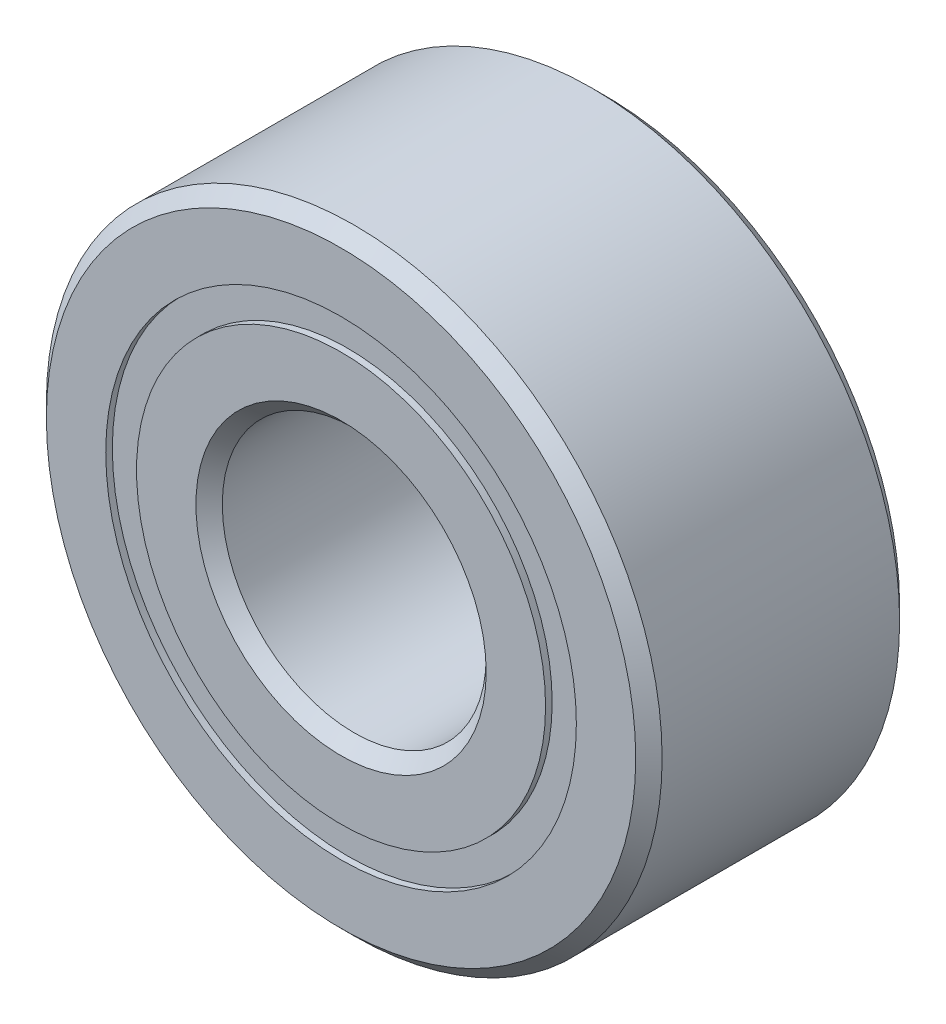
SolidWorks part; units mm, degrees
material "Chrome Stainless Steel"
ref_plane "Front Plane" through (0, 0, 0) normal (0, 0, 1) x (1, 0, 0)
ref_plane "Top Plane" through (0, 0, 0) normal (0, 1, 0) x (1, 0, 0)
ref_plane "Right Plane" through (0, 0, 0) normal (1, 0, 0) x (0, 0, -1)
sketch "Sketch3" plane through (0, 0, 0) normal (0, 1, 0) x (1, 0, 0)
  line L0 (1.5, -1.5) -> (1.5, 1.5)
  line L1 (1.5, 1.5) -> (2.325, 1.5)
  line L2 (2.325, 1.5) -> (2.325, 1.425)
  line L3 (2.325, 1.425) -> (2.675, 1.425)
  line L4 (2.675, 1.425) -> (2.675, 1.5)
  line L5 (2.675, 1.5) -> (3.5, 1.5)
  line L6 (3.5, 1.5) -> (3.5, -1.5)
  line L7 (-55, 0) -> (55, 0) construction
  line L8 (2.675, -1.5) -> (3.5, -1.5)
  line L9 (2.675, -1.425) -> (2.675, -1.5)
  line L10 (2.325, -1.425) -> (2.675, -1.425)
  line L11 (2.325, -1.5) -> (2.325, -1.425)
  line L12 (1.5, -1.5) -> (2.325, -1.5)
  line L13 (0, 0) -> (0, 50000) construction
  point P11 (3.5, 0)
  point P16 (1.5, 0)
  dimension "D1" = 3
  dimension "D2" = 3
  dimension "D3" = 2.85
  dimension "D4" = 4.65
  dimension "D5" = 5.35
  dimension "D6" = 7
revolve "Revolve1" add sketch "Sketch3" angle 360 about L13
chamfer "Chamfer1" distance 0.15 angle 45 4 edges at (1.5, 0, -1.5) (1.5, 0, 1.5) (3.5, 0, 1.5) (3.5, 0, -1.5)
